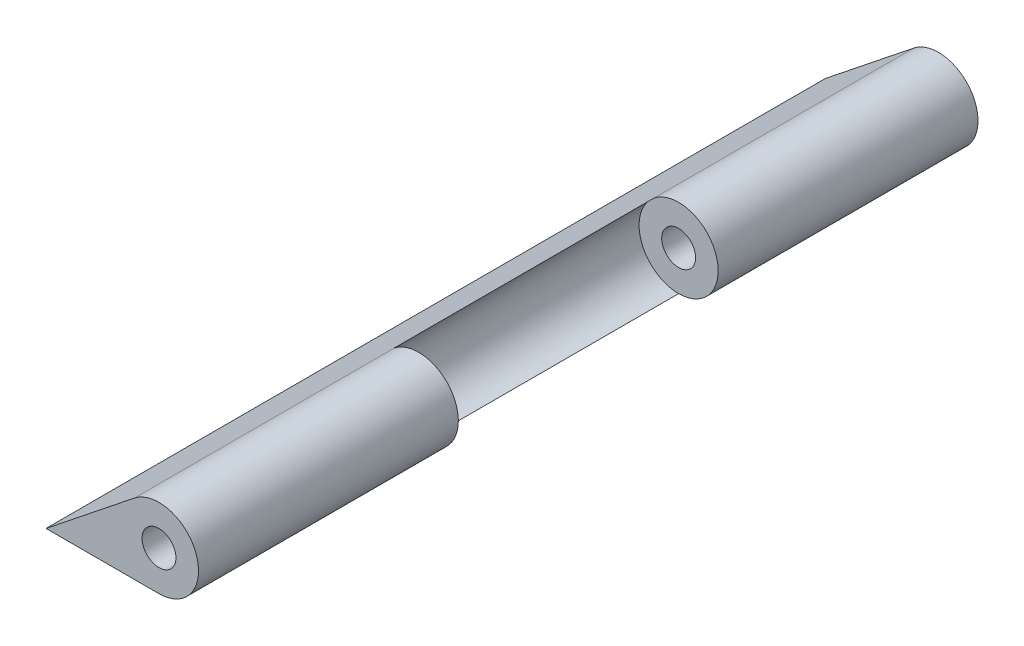
SolidWorks part; units mm, degrees
ref_plane "Front Plane" through (0, 0, 0) normal (0, 0, 1) x (1, 0, 0)
ref_plane "Top Plane" through (0, 0, 0) normal (0, 1, 0) x (1, 0, 0)
ref_plane "Right Plane" through (0, 0, 0) normal (1, 0, 0) x (0, 0, -1)
sketch "Sketch1" plane through (0, 0, 0) normal (0, 0, 1) x (1, 0, 0)
  circle A0 centre (0, 0) radius 3.5
  circle A1 centre (0, 0) radius 1.5
  dimension "D1" = 7
  dimension "D2" = 2
extrude "Boss-Extrude1" add sketch "Sketch1" along normal mid plane 69
sketch "Sketch2" plane through (0, 0, 0) normal (0, 0, 1) x (1, 0, 0)
  line L0 (0, -3.5) -> (-10, -3.5)
  line L1 (-10, -3.5) -> (-2.1826, 2.7361)
  line L2 (0, 0) -> (0, -3.5) construction
  circle A0 centre (0, 0) radius 3.5 construction
  arc A1 (-2.1826, 2.7361) -> (0, -3.5) centre (0, 0) ccw
  dimension "D1" = 10
extrude "Boss-Extrude2" add sketch "Sketch2" along normal mid plane 69
sketch "Sketch5" plane through (0, 0, 0) normal (0, 0, 1) x (1, 0, 0)
  circle A0 centre (0, 0) radius 3.5
  dimension "D1" = 7
extrude "Cut-Extrude1" cut sketch "Sketch5" against normal mid plane 23
